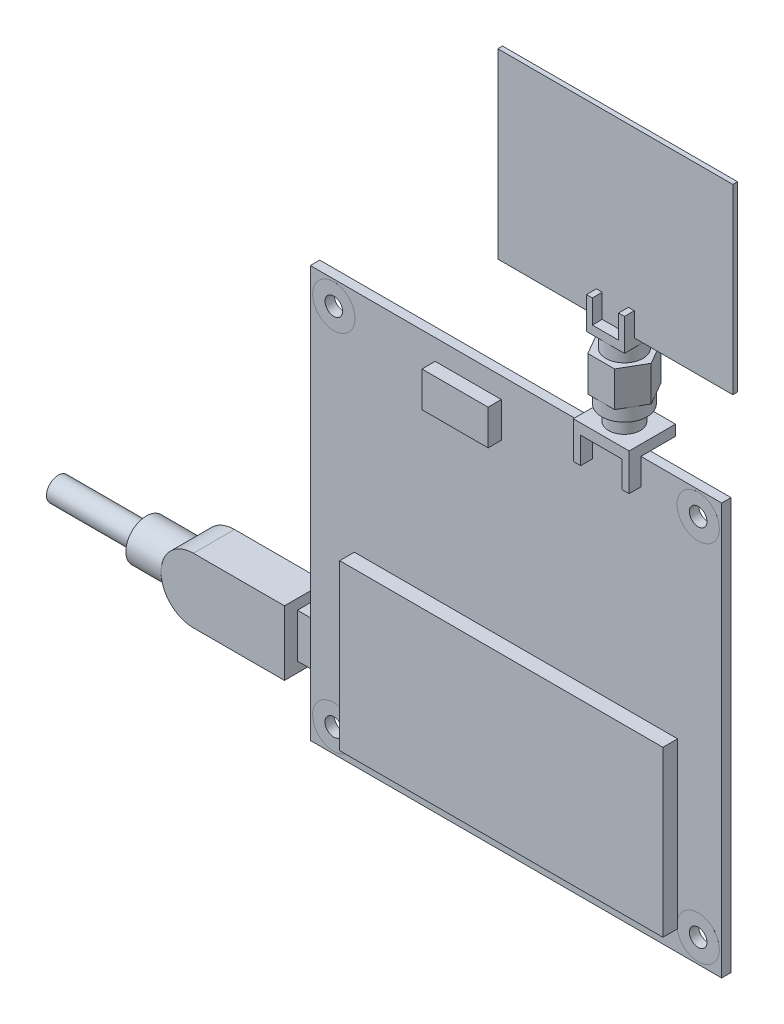
SolidWorks part; units mm, degrees
ref_plane "Front Plane" through (0, 0, 0) normal (0, 0, 1) x (1, 0, 0)
ref_plane "Top Plane" through (0, 0, 0) normal (0, 1, 0) x (1, 0, 0)
ref_plane "Right Plane" through (0, 0, 0) normal (1, 0, 0) x (0, 0, -1)
sketch "Sketch1" plane through (0, 0, 0) normal (0, 0, 1) x (1, 0, 0)
  line L1 (0, 0) -> (70, 0)
  line L2 (0, 0) -> (0, 70)
  line L3 (0, 70) -> (70, 70)
  line L4 (70, 0) -> (70, 70)
  dimension "D1" = 70
  dimension "D2" = 70
extrude "Green PCB" add sketch "Sketch1" along normal mid plane 1.6
sketch "Sketch2" plane through (0, 0, 0.8) normal (0, 0, 1) x (1, 0, 0)
  line L0 (70, 0) -> (70, 70) construction
  line L1 (4, 66) -> (66, 66) construction
  line L2 (4, 66) -> (4, 4) construction
  line L3 (4, 4) -> (66, 4) construction
  line L4 (66, 66) -> (66, 4) construction
  line L5 (70, 70) -> (0, 70) construction
  line L6 (0, 70) -> (0, 0) construction
  line L7 (0, 0) -> (70, 0) construction
  circle A0 centre (4, 4) radius 1.5
  circle A1 centre (66, 4) radius 1.5
  circle A2 centre (66, 66) radius 1.5
  circle A3 centre (4, 66) radius 1.5
  dimension "D1" = 3
  dimension "D2" = 4
  dimension "D3" = 4
  dimension "D4" = 4
  dimension "D5" = 4
extrude "Mounting Holes" cut sketch "Sketch2" against normal through all
sketch "Sketch3" plane through (0, 0, 0) normal (0, 0, 1) x (1, 0, 0)
  circle A0 centre (4, 66) radius 3.6
  circle A1 centre (66, 66) radius 3.6
  circle A2 centre (66, 4) radius 3.6
  circle A3 centre (4, 4) radius 3.6
  circle A4 centre (4, 66) radius 1.5
  circle A5 centre (66, 66) radius 1.5
  circle A6 centre (66, 4) radius 1.5
  circle A7 centre (4, 4) radius 1.5
  circle A8 centre (4, 4) radius 1.5 construction
  circle A9 centre (66, 4) radius 1.5 construction
  circle A10 centre (66, 66) radius 1.5 construction
  circle A11 centre (4, 66) radius 1.5 construction
  dimension "D1" = 7.2
extrude "Screw Grounds" add sketch "Sketch3" along normal offset from surface 0.001 and the other way offset from surface (0.801 mm away) 0.001 up to face at (5.5, 66, 0.8) offset beyond the face yes other way up to face at (5.5, 66, -0.8)
sketch "Sketch4" plane through (0, 70, 0) normal (0, 1, 0) x (1, 0, 0)
  line L0 (70, -0.8) -> (70, 0.8) construction
  line L1 (46.75, 5.1) -> (56.25, 5.1)
  line L2 (46.75, 5.1) -> (46.75, -2.8)
  line L3 (46.75, -2.8) -> (56.25, -2.8)
  line L4 (56.25, 5.1) -> (56.25, -2.8)
  line L5 (70, -0.8) -> (0, -0.8) construction
  dimension "D1" = 7.9
  dimension "D2" = 9.5
  dimension "D3" = 13.75
  dimension "D4" = 2
extrude "Antenna1" add sketch "Sketch4" along normal blind 1.8
sketch "Sketch10" plane through (0, 0, 2.8) normal (0, 0, 1) x (1, 0, 0)
  line L1 (46.75, 70) -> (48, 70)
  line L2 (46.75, 70) -> (46.75, 65.5)
  line L3 (46.75, 65.5) -> (48, 65.5)
  line L4 (48, 70) -> (48, 65.5)
  line L5 (56.25, 70) -> (55, 70)
  line L6 (56.25, 70) -> (56.25, 65.5)
  line L7 (56.25, 65.5) -> (55, 65.5)
  line L8 (55, 70) -> (55, 65.5)
  dimension "D1" = 1.25
  dimension "D2" = 4.5
extrude "Antenna2" add sketch "Sketch10" against normal up to surface (2 mm away) up to face at (62.4, 4, 0.8)
sketch "Sketch5" plane through (0, 71.8, 0) normal (0, 1, 0) x (1, 0, 0)
  line L0 (56.25, 5.1) -> (46.75, -2.8) construction
  circle A0 centre (51.5, 1.15) radius 2.7
  dimension "D1" = 5.4
extrude "Antenna3" add sketch "Sketch5" along normal blind 2.6
sketch "Sketch6" plane through (0, 74.4, 0) normal (0, 1, 0) x (1, 0, 0)
  circle A0 centre (51.5, 1.15) radius 3.85
  dimension "D1" = 7.7
extrude "Antenna4" add sketch "Sketch6" along normal blind 2.25
sketch "Sketch7" plane through (0, 76.65, 0) normal (0, 1, 0) x (1, 0, 0)
  line L0 (46.75, -2.8) -> (56.25, -2.8) construction
  line L1 (49.2195, -2.8) -> (53.7805, -2.8)
  line L2 (53.7805, -2.8) -> (56.0611, 1.15)
  line L3 (56.0611, 1.15) -> (53.7805, 5.1)
  line L4 (53.7805, 5.1) -> (49.2195, 5.1)
  line L5 (49.2195, 5.1) -> (46.9389, 1.15)
  line L6 (46.9389, 1.15) -> (49.2195, -2.8)
  circle A0 centre (51.5, 1.15) radius 3.95 construction
  dimension "D1" = 7.9
extrude "Antenna5" add sketch "Sketch7" along normal blind 6
sketch "Sketch8" plane through (0, 82.65, 0) normal (0, 1, 0) x (1, 0, 0)
  circle A0 centre (51.5, 1.15) radius 3.15
  dimension "D1" = 6.3
extrude "Antenna6" add sketch "Sketch8" along normal blind 2.4
sketch "Sketch9" plane through (0, 85.05, 0) normal (0, 1, 0) x (1, 0, 0)
  line L1 (54.725, 4.375) -> (48.275, 4.375)
  line L2 (54.725, 4.375) -> (54.725, -2.075)
  line L3 (54.725, -2.075) -> (48.275, -2.075)
  line L4 (48.275, 4.375) -> (48.275, -2.075)
  line L5 (54.725, 4.375) -> (48.275, -2.075) construction
  line L6 (54.725, -2.075) -> (48.275, 4.375) construction
  point P0 (51.5, 1.15)
  dimension "D1" = 6.45
  dimension "D2" = 6.45
extrude "Antenna7" add sketch "Sketch9" along normal blind 1.45
sketch "Sketch11" plane through (0, 86.5, 0) normal (0, 1, 0) x (1, 0, 0)
  line L0 (71.5, 0) -> (31.5, 0) construction
  line L1 (71.5, 0.4) -> (31.5, 0.4)
  line L2 (71.5, 0.4) -> (71.5, -0.4)
  line L3 (71.5, -0.4) -> (31.5, -0.4)
  line L4 (31.5, 0.4) -> (31.5, -0.4)
  line L5 (-38.5, 0) -> (38.5, 0) construction
  line L6 (51.5, 4.375) -> (51.5, -2.075) construction
  line L7 (54.725, 4.375) -> (48.275, 4.375) construction
  line L8 (48.275, -2.075) -> (54.725, -2.075) construction
  point P14 (51.5, 0)
  dimension "D1" = 40
  dimension "D2" = 0.8
extrude "Antenna PCB" add sketch "Sketch11" along normal blind 31
sketch "Sketch19" plane through (0, 0, 2.075) normal (0, 0, 1) x (1, 0, 0)
  line L0 (48.275, 86.5) -> (48.275, 85.05) construction
  line L1 (48.275, 86.5) -> (49.275, 86.5)
  line L2 (48.275, 86.5) -> (48.275, 90.5)
  line L3 (48.275, 90.5) -> (49.275, 90.5)
  line L4 (49.275, 86.5) -> (49.275, 90.5)
  line L5 (48.275, 86.5) -> (54.725, 86.5) construction
  line L7 (54.725, 86.5) -> (53.725, 86.5)
  line L8 (54.725, 86.5) -> (54.725, 90.5)
  line L9 (54.725, 90.5) -> (53.725, 90.5)
  line L10 (53.725, 86.5) -> (53.725, 90.5)
  dimension "D1" = 1
  dimension "D2" = 4
extrude "Antenna8" add sketch "Sketch19" against normal up to surface (1.675 mm away) up to face at (51.5, 96.8333, 0.4)
sketch "Sketch12" plane through (0, 0, 0.8) normal (0, 0, 1) x (1, 0, 0)
  line L0 (0, 0) -> (70, 0) construction
  line L1 (7.5, 3.5) -> (62.5, 3.5)
  line L2 (7.5, 3.5) -> (7.5, 31.5)
  line L3 (7.5, 31.5) -> (62.5, 31.5)
  line L4 (62.5, 3.5) -> (62.5, 31.5)
  line L5 (35, 3.5) -> (35, 31.5) construction
  line L6 (0, 17.5) -> (70, 17.5) construction
  line L7 (0, 70) -> (0, 0) construction
  line L8 (70, 0) -> (70, 70) construction
  point P14 (35, 17.5)
  point P15 (35, 17.5)
  dimension "D1" = 55
  dimension "D2" = 28
  dimension "D3" = 3.5
extrude "LCD" add sketch "Sketch12" along normal blind 2.5
sketch "Sketch13" plane through (0, 0, 0.8) normal (0, 0, 1) x (1, 0, 0)
  line L0 (0, 70) -> (0, 0) construction
  line L1 (21.25, 66.5) -> (32.5, 66.5)
  line L2 (21.25, 66.5) -> (21.25, 60.5)
  line L3 (21.25, 60.5) -> (32.5, 60.5)
  line L4 (32.5, 66.5) -> (32.5, 60.5)
  line L5 (46.75, 70) -> (0, 70) construction
  dimension "D1" = 11.25
  dimension "D2" = 6
  dimension "D3" = 32.5
  dimension "D4" = 9.5
extrude "Option Switch" add sketch "Sketch13" along normal blind 2.25
sketch "Sketch14" plane through (0, 0, -0.8) normal (0, 0, -1) x (-1, 0, 0)
  line L0 (0, 0) -> (-70, 0) construction
  line L1 (-4, 16.5) -> (3.8, 16.5)
  line L2 (-4, 16.5) -> (-4, 9)
  line L3 (-4, 9) -> (3.8, 9)
  line L4 (3.8, 16.5) -> (3.8, 9)
  line L6 (0, 70) -> (0, 0) construction
  dimension "D1" = 7.5
  dimension "D2" = 7.8
  dimension "D3" = 16.5
  dimension "D4" = 4
extrude "USB Port" add sketch "Sketch14" along normal blind 2.6
ref_plane "Plane1" through (0, 0, -2.1) normal (0, 0, -1) x (-1, 0, 0)
sketch "Sketch16" plane through (0, 0, -2.1) normal (0, 0, -1) x (-1, 0, 0)
  line L0 (19.3, 7.25) -> (3.8, 7.25)
  line L1 (3.8, 7.25) -> (3.8, 18.25)
  line L2 (3.8, 18.25) -> (19.3, 18.25)
  line L3 (3.8, 16.5) -> (3.8, 9) construction
  arc A1 (19.3, 7.25) -> (19.3, 18.25) centre (19.3, 12.75) ccw
  point P7 (3.8, 12.75)
  dimension "D1" = 11
  dimension "D2" = 21
extrude "USB Body" add sketch "Sketch16" along normal mid plane 7
ref_plane "Plane2" through (-24.8, 0, 0) normal (-1, 0, 0) x (0, 0, 1)
sketch "Sketch17" plane through (-24.8, 0, 0) normal (-1, 0, 0) x (0, 0, 1)
  line L0 (-5.6, 18.25) -> (-5.6, 7.25) construction
  line L2 (1.4, 12.75) -> (-5.6, 12.75) construction
  line L3 (1.4, 7.25) -> (1.4, 18.25) construction
  circle A0 centre (-2.1, 12.75) radius 3.5
  point P4 (-5.6, 12.75)
  point P12 (-2.1, 12.75)
  point P16 (1.4, 12.75)
extrude "USB Tension Relief" add sketch "Sketch17" along normal blind 6 and the other way up to surface (6 mm away)
sketch "Sketch18" plane through (-30.8, 0, 0) normal (-1, 0, 0) x (0, 0, 1)
  circle A0 centre (-2.1, 12.75) radius 2
  dimension "D1" = 4
extrude "USB Cord" add sketch "Sketch18" along normal blind 15
